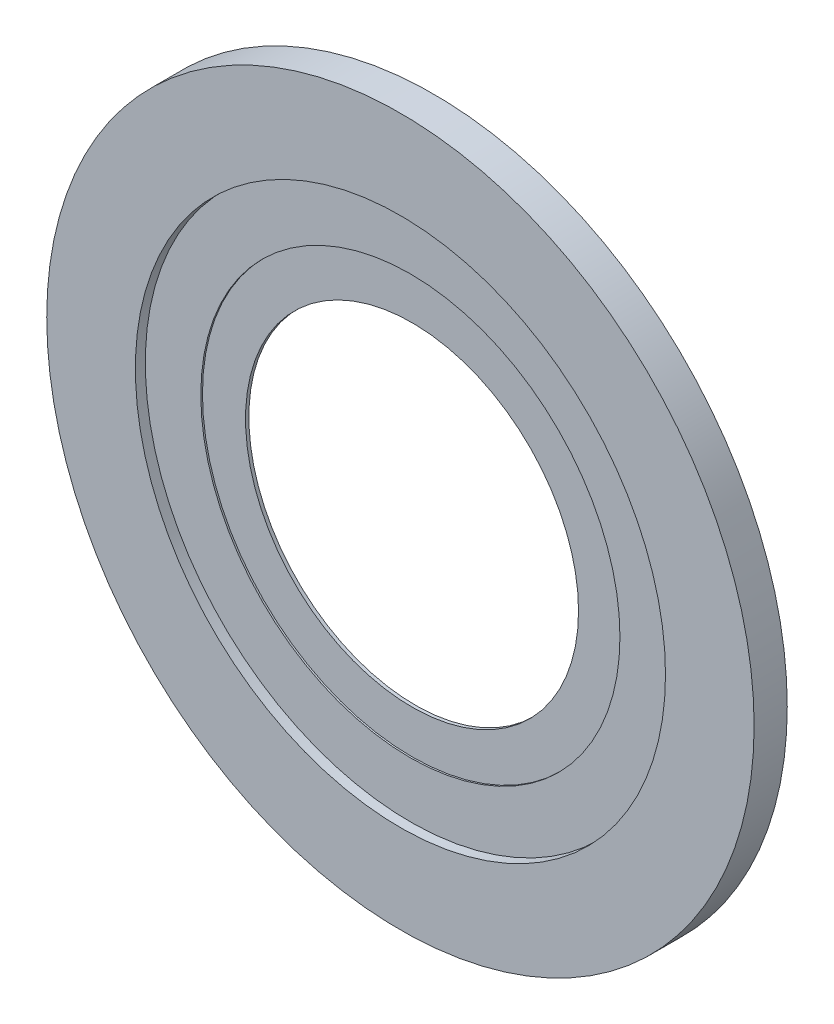
SolidWorks part; units mm, degrees
material "1.4016 (X6Cr17)"
ref_plane "Ebene vorne" through (0, 0, 0) normal (0, 0, 1) x (1, 0, 0)
ref_plane "Ebene oben" through (0, 0, 0) normal (0, 1, 0) x (1, 0, 0)
ref_plane "Ebene rechts" through (0, 0, 0) normal (1, 0, 0) x (0, 0, -1)
sketch "Skizze2" plane through (0, 0, 0) normal (0, 0, 1) x (1, 0, 0)
  circle A0 centre (0, 0) radius 21.35
  dimension "D1" = 42.7
extrude "Aufsatz-Linear austragen1" add sketch "Skizze2" along normal blind 2
sketch "Skizze3" plane through (0, 0, 2) normal (0, 0, 1) x (1, 0, 0)
  line L0 (0, 0) -> (-21.35, 0) construction
  line L1 (0, 0) -> (10.675, 18.4896) construction
  line L2 (0, 0) -> (10.675, -18.4896) construction
  circle A0 centre (0, 0) radius 21.35 construction
  dimension "D1" = 120
  dimension "D2" = 120
sketch "Skizze6" plane through (0, 0, 2) normal (0, 0, 1) x (1, 0, 0)
  circle A0 centre (0, 0) radius 10.05
  dimension "D1" = 20.1
extrude "Schnitt-Linear austragen4" cut sketch "Skizze6" against normal through all
sketch "Skizze7" plane through (0, 0, 2) normal (0, 0, 1) x (1, 0, 0)
  circle A0 centre (0, 0) radius 16
  dimension "D1" = 32
extrude "Schnitt-Linear austragen5" cut sketch "Skizze7" against normal blind 0.6
chamfer "Fase1" distance 1.1 angle 80 1 edges at (10.05, 0, 0)
sketch "Skizze8" plane through (0, 0, 1.4) normal (0, 0, 1) x (1, 0, 0)
  circle A0 centre (0, 0) radius 12.65
  dimension "D1" = 25.3
extrude "Schnitt-Linear austragen6" cut sketch "Skizze8" against normal blind 0.1
